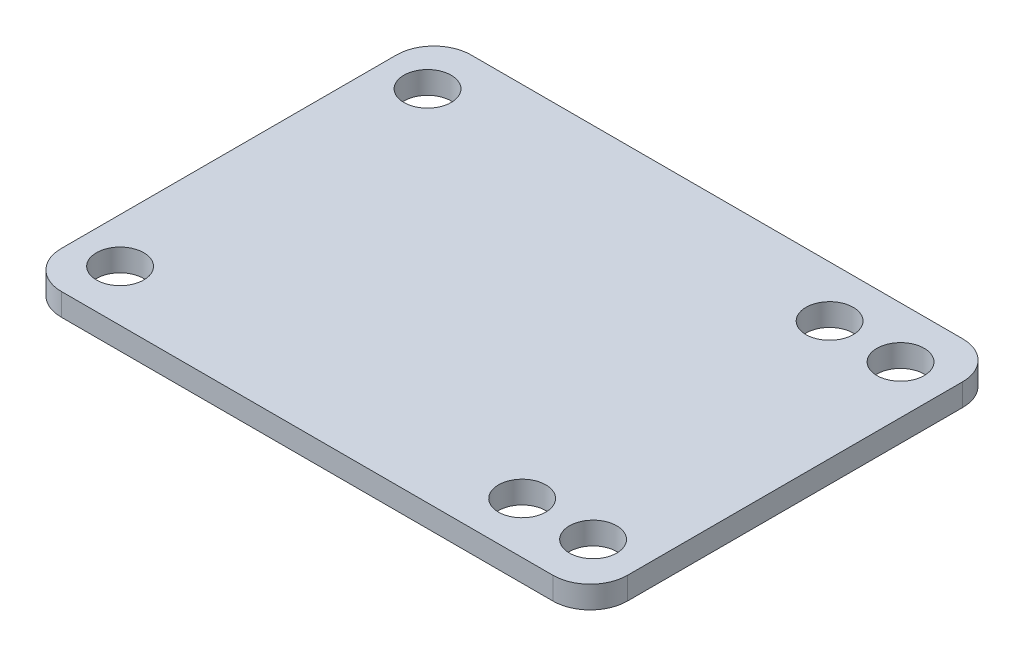
SolidWorks part; units mm, degrees
material "Rubber"
ref_plane "Front Plane" through (0, 0, 0) normal (0, 0, 1) x (1, 0, 0)
ref_plane "Top Plane" through (0, 0, 0) normal (0, 1, 0) x (1, 0, 0)
ref_plane "Right Plane" through (0, 0, 0) normal (1, 0, 0) x (0, 0, -1)
sketch "Sketch1" plane through (0, 0, 0) normal (0, 1, 0) x (1, 0, 0)
  line L1 (0, 0) -> (76, 0)
  line L2 (0, 0) -> (0, 55)
  line L3 (0, 55) -> (76, 55)
  line L4 (76, 0) -> (76, 55)
  dimension "D1" = 76
  dimension "D2" = 55
extrude "Boss-Extrude1" add sketch "Sketch1" along normal blind 3
fillet "Fillet2" radius 5 4 edges at (76, 1.5, 0) (0, 1.5, 0) (0, 1.5, -55) (76, 1.5, -55)
sketch "Sketch2" plane through (0, 3, 0) normal (0, 1, 0) x (1, 0, 0)
  line L0 (0, 50) -> (0, 5) construction
  line L4 (6.025, 48.1375) -> (69.525, 48.1375) construction
  line L5 (6.025, 48.1375) -> (6.025, 6.8625) construction
  line L6 (6.025, 6.8625) -> (69.525, 6.8625) construction
  line L7 (69.525, 48.1375) -> (69.525, 6.8625) construction
  line L8 (76, 5) -> (76, 50) construction
  circle A2 centre (6.025, 48.1375) radius 3.175
  circle A3 centre (60, 48.1375) radius 3.175
  circle A4 centre (69.525, 48.1375) radius 3.175
  circle A5 centre (69.525, 6.8625) radius 3.175
  circle A6 centre (60, 6.8625) radius 3.175
  circle A7 centre (6.025, 6.8625) radius 3.175
  point P5 (60, 48.1375)
  point P6 (60, 6.8625)
  point P7 (6.025, 27.5)
  point P8 (0, 27.5)
  point P23 (0, 0)
  dimension "D5" = 6.35
  dimension "D1" = 41.275
  dimension "D2" = 53.975
  dimension "D3" = 63.5
  dimension "D4" = 16
extrude "Cut-Extrude1" cut sketch "Sketch2" against normal through all
